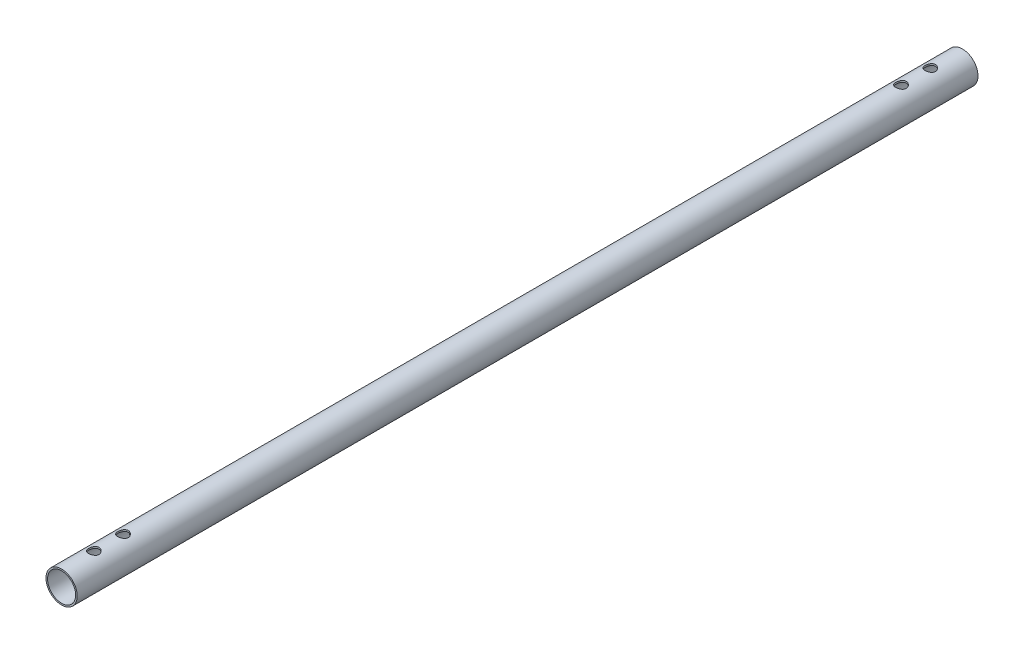
SolidWorks part; units mm, degrees
material "Galvanized Steel"
ref_plane "Front Plane" through (0, 0, 0) normal (0, 0, 1) x (1, 0, 0)
ref_plane "Top Plane" through (0, 0, 0) normal (0, 1, 0) x (1, 0, 0)
ref_plane "Right Plane" through (0, 0, 0) normal (1, 0, 0) x (0, 0, -1)
sketch "Sketch1" plane through (0, 0, 0) normal (0, 0, 1) x (1, 0, 0)
  circle A0 centre (0, 0) radius 13.35
  circle A1 centre (0, 0) radius 11.7
  dimension "D1" = 26.7
  dimension "D2" = 23.4
extrude "Boss-Extrude1" add sketch "Sketch1" along normal blind 770
sketch "Sketch2" plane through (0, 0, 770) normal (0, 0, 1) x (1, 0, 0)
  circle A0 centre (0, 0) radius 12
  dimension "D1" = 24
extrude "Cut-Extrude1" cut sketch "Sketch2" against normal blind 70
sketch "Sketch3" plane through (0, 0, 0) normal (0, 0, -1) x (-1, 0, 0)
  circle A0 centre (0, 0) radius 12
  dimension "D1" = 24
extrude "Cut-Extrude2" cut sketch "Sketch3" against normal blind 70
sketch "Sketch4" plane through (0, 0, 0) normal (0, 1, 0) x (1, 0, 0)
  line L0 (12, 0) -> (-12, 0) construction
  circle A0 centre (0, -27.5) radius 4.5
  dimension "D1" = 9
  dimension "D2" = 27.5
extrude "Cut-Extrude3" cut sketch "Sketch4" against normal through all both and the other way through all
pattern_linear "LPattern1" count 2 spacing 25 along (0, 0, 1) of "Cut-Extrude3"
ref_plane "Plane1" through (0, 0, 385) normal (0, 0, -1) x (-1, 0, 0)
mirror "Mirror1" about plane through (0, 0, 385) normal (0, 0, -1) of "LPattern1", "Cut-Extrude3"
